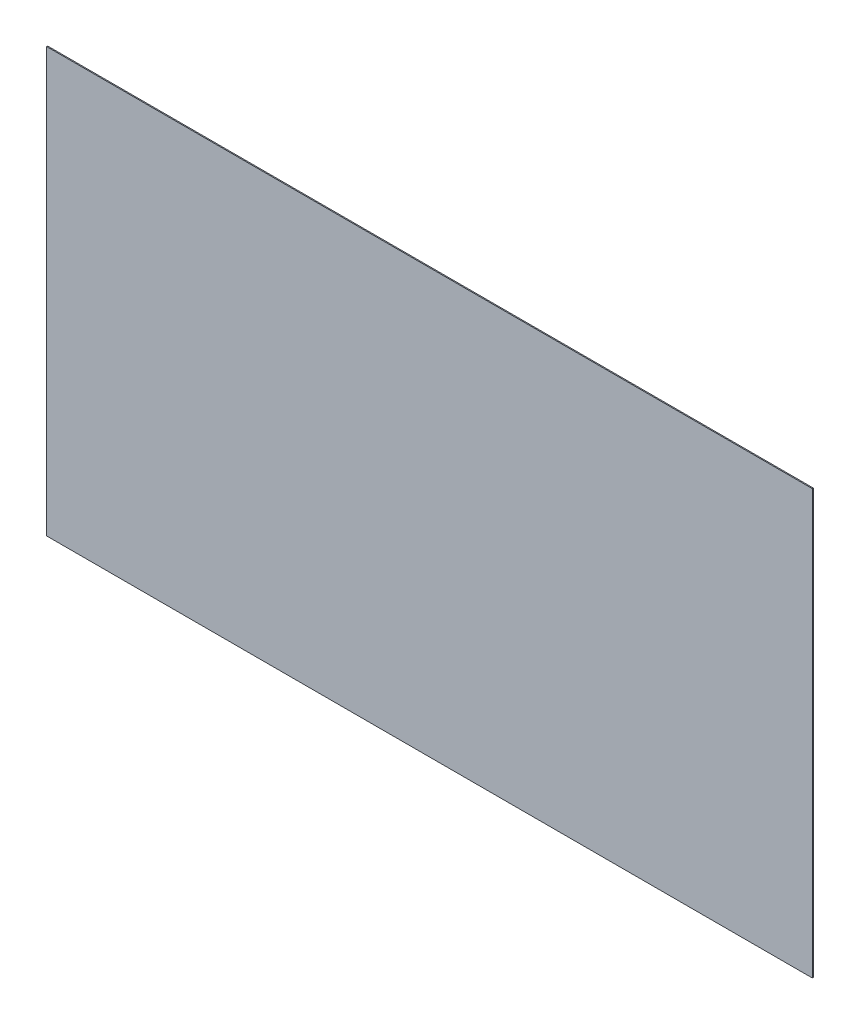
SolidWorks part; units mm, degrees
ref_plane "Front Plane" through (0, 0, 0) normal (0, 0, 1) x (1, 0, 0)
ref_plane "Top Plane" through (0, 0, 0) normal (0, 1, 0) x (1, 0, 0)
ref_plane "Right Plane" through (0, 0, 0) normal (1, 0, 0) x (0, 0, -1)
sketch "Sketch1" plane through (0, 0, 0) normal (0, 0, 1) x (1, 0, 0)
  line L1 (560, 310) -> (-560, 310)
  line L2 (560, 310) -> (560, -310)
  line L3 (560, -310) -> (-560, -310)
  line L4 (-560, 310) -> (-560, -310)
  line L5 (560, 310) -> (-560, -310) construction
  line L6 (560, -310) -> (-560, 310) construction
  point P0 (0, 0)
  dimension "D1" = 1120
  dimension "D2" = 620
extrude "Boss-Extrude1" add sketch "Sketch1" along normal blind 1.5
